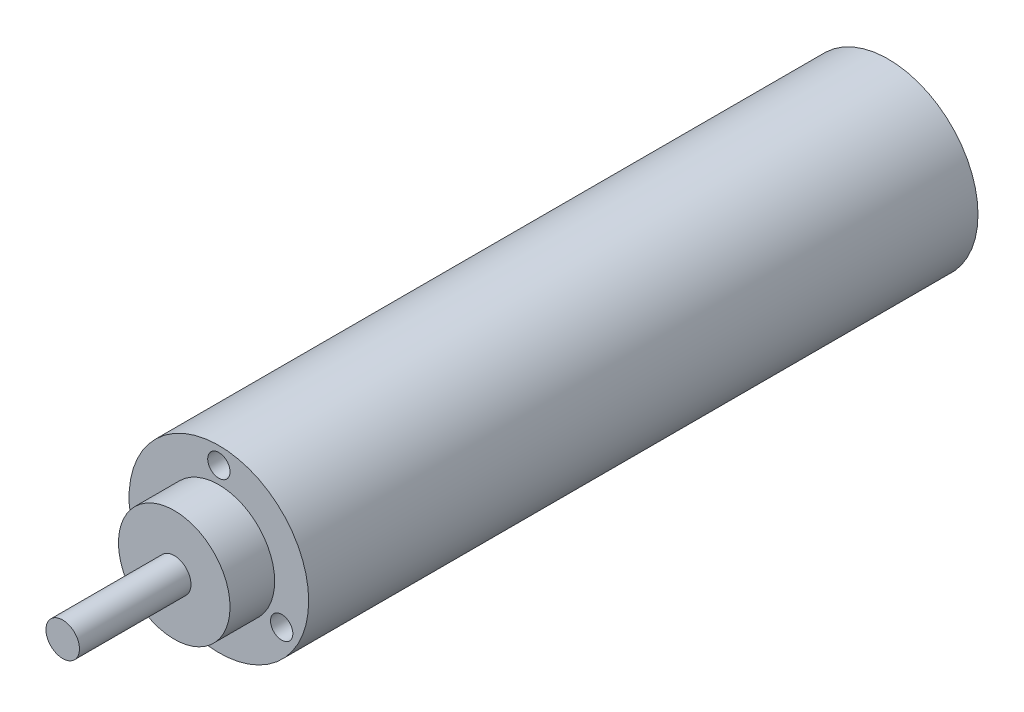
SolidWorks part; units mm, degrees
material "Titanium Ti-8Al-1Mo-1V"
ref_plane "Front" through (0, 0, 0) normal (0, 0, 1) x (1, 0, 0)
ref_plane "Top" through (0, 0, 0) normal (0, 1, 0) x (1, 0, 0)
ref_plane "Right" through (0, 0, 0) normal (1, 0, 0) x (0, 0, -1)
sketch "Sketch1" plane through (0, 0, 0) normal (0, 0, 1) x (1, 0, 0)
  circle A0 centre (0, 0) radius 8.05
extrude "Boss-Extrude1" add sketch "Sketch1" along normal blind 60
sketch "Sketch2" plane through (0, 0, 60) normal (0, 0, 1) x (1, 0, 0)
  circle A0 centre (0, 0) radius 5
extrude "Boss-Extrude2" add sketch "Sketch2" along normal blind 4
sketch "Sketch3" plane through (0, 0, 60) normal (0, 0, 1) x (1, 0, 0)
  line L0 (0, 0) -> (0, 8.05) construction
  line L1 (0, 0) -> (-6.9715, -4.025) construction
  line L2 (0, 0) -> (6.9715, -4.025) construction
  circle A0 centre (0, 0) radius 8.05 construction
  circle A1 centre (0, 6.5) radius 1
  circle A2 centre (5.6292, -3.25) radius 1
  circle A3 centre (-5.6292, -3.25) radius 1
  dimension "D3" = 6.5
  dimension "D1" = 120
  dimension "D2" = 120
  dimension "D4" = 6.5
  dimension "D5" = 6.5
extrude "Cut-Extrude1" cut sketch "Sketch3" against normal blind 5
sketch "Sketch4" plane through (0, 0, 64) normal (0, 0, 1) x (1, 0, 0)
  circle A0 centre (0, 0) radius 1.5
extrude "Boss-Extrude3" add sketch "Sketch4" along normal blind 10
